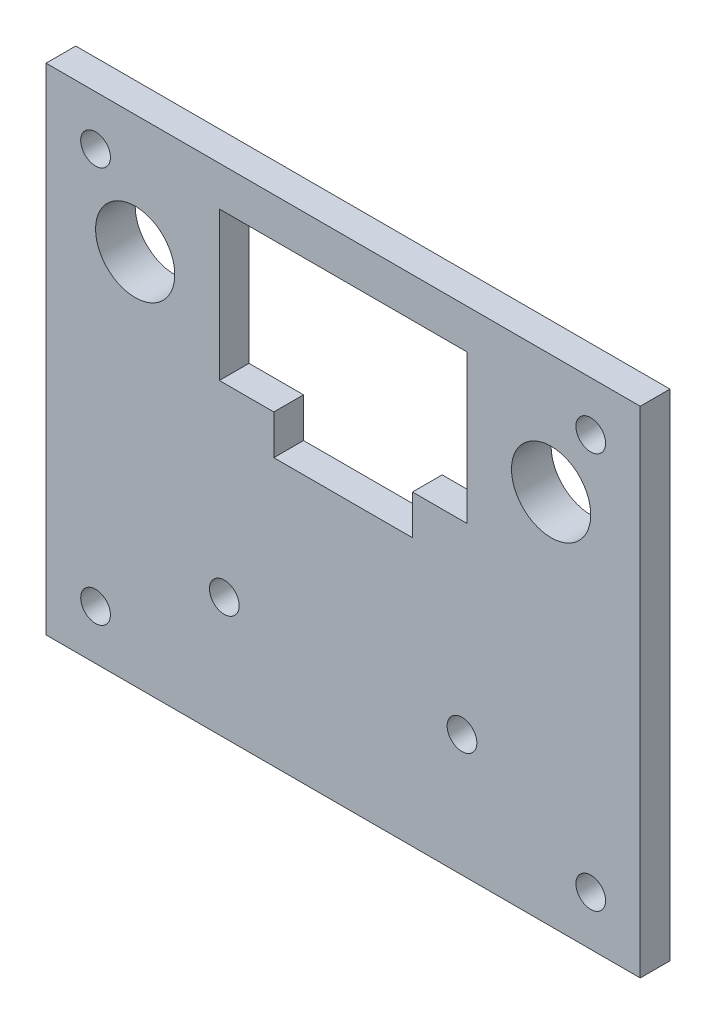
SolidWorks part; units mm, degrees
ref_plane "Front Plane" through (0, 0, 0) normal (0, 0, 1) x (1, 0, 0)
ref_plane "Top Plane" through (0, 0, 0) normal (0, 1, 0) x (1, 0, 0)
ref_plane "Right Plane" through (0, 0, 0) normal (1, 0, 0) x (0, 0, -1)
sketch "Sketch1" plane through (0, 0, 0) normal (0, 0, 1) x (1, 0, 0)
  line L1 (-30, -25) -> (30, -25)
  line L2 (-30, -25) -> (-30, 25)
  line L3 (-30, 25) -> (30, 25)
  line L4 (30, -25) -> (30, 25)
  line L5 (-30, -25) -> (30, 25) construction
  line L6 (-30, 25) -> (30, -25) construction
  point P0 (0, 0)
  dimension "D1" = 60
  dimension "D2" = 50
extrude "Boss-Extrude1" add sketch "Sketch1" along normal blind 3
sketch "Sketch2" plane through (0, 0, 0) normal (0, 0, -1) x (-1, 0, 0)
  line L0 (0, 0) -> (0, 25.8564) construction
  line L1 (-30, 25) -> (30, 25) construction
  circle A0 centre (21, 13) radius 4
  circle A1 centre (-21, 13) radius 4
  dimension "D3" = 8
  dimension "D1" = 42
  dimension "D2" = 12
extrude "Cut-Extrude1" cut sketch "Sketch2" against normal through all
sketch "Sketch3" plane through (0, 0, 0) normal (0, 0, -1) x (-1, 0, 0)
  circle A0 centre (21, 13) radius 5
  circle A1 centre (21, 13) radius 4
  circle A2 centre (-21, 13) radius 5
  circle A3 centre (-21, 13) radius 4
  dimension "D1" = 8
  dimension "D2" = 8
  dimension "D3" = 10
  dimension "D4" = 10
  dimension "D5" = 42
extrude "Boss-Extrude2" add sketch "Sketch3" along normal blind 1
sketch "Sketch4" plane through (0, 0, 0) normal (0, 0, -1) x (-1, 0, 0)
  line L0 (-12.5, 21) -> (12.5, 21)
  line L2 (-12.5, 21) -> (-12.5, 6)
  line L5 (12.5, 21) -> (12.5, 6)
  line L6 (12.5, 6) -> (-12.5, 6)
  line L7 (-30, -25) -> (-30, 25) construction
  line L8 (30, 25) -> (30, -25) construction
  line L9 (-30, 25) -> (30, 25) construction
  dimension "D1" = 25
  dimension "D2" = 17.5
  dimension "D3" = 17.5
  dimension "D4" = 4
extrude "Cut-Extrude2" cut sketch "Sketch4" against normal through all
sketch "Sketch5" plane through (0, 0, 0) normal (0, 0, -1) x (-1, 0, 0)
  line L1 (-7, 6) -> (7, 6)
  line L2 (-7, 6) -> (-7, 2)
  line L3 (-7, 2) -> (7, 2)
  line L4 (7, 6) -> (7, 2)
  line L6 (-12.5, 21) -> (-12.5, 6) construction
  dimension "D2" = 14
  dimension "D3" = 5.5
  dimension "D4" = 4
extrude "Cut-Extrude3" cut sketch "Sketch5" against normal through all
sketch "Sketch6" plane through (0, 0, 0) normal (0, 0, -1) x (-1, 0, 0)
  line L0 (30, -25) -> (-30, -25) construction
  line L1 (-7.0006, -2.2866) -> (7.4227, -2.2866)
  line L2 (-7.0006, -2.2866) -> (-7.0006, -25)
  line L3 (-7.0006, -25) -> (7.4227, -25)
  line L4 (7.4227, -2.2866) -> (7.4227, -25)
extrude "Boss-Extrude3" add sketch "Sketch6" along normal blind 3.3
sketch "Sketch8" plane through (0, 0, 0) normal (0, 0, -1) x (-1, 0, 0)
  line L0 (0, 0) -> (0, 24.7307) construction
  line L1 (0, 0) -> (-31.9071, 0) construction
  line L2 (-30, 25) -> (30, 25) construction
  line L3 (-30, -25) -> (-30, 25) construction
  circle A0 centre (-25, 20) radius 1.5
  circle A1 centre (-25, -20) radius 1.5
  circle A2 centre (25, -20) radius 1.5
  circle A3 centre (25, 20) radius 1.5
  dimension "D1" = 3
  dimension "D3" = 5
  dimension "D2" = 5
extrude "Cut-Extrude4" cut sketch "Sketch8" against normal through all
sketch "Sketch9" plane through (0, 0, 0) normal (0, 0, -1) x (-1, 0, 0)
  line L0 (0, 0) -> (0, -27.6153) construction
  line L1 (-7.0006, -2.2866) -> (-7.0006, -25) construction
  circle A0 centre (-12.0006, -12.6995) radius 1.5
  circle A1 centre (12.0006, -12.6995) radius 1.5
  dimension "D1" = 3
  dimension "D2" = 5
extrude "Cut-Extrude5" cut sketch "Sketch9" against normal blind 10
